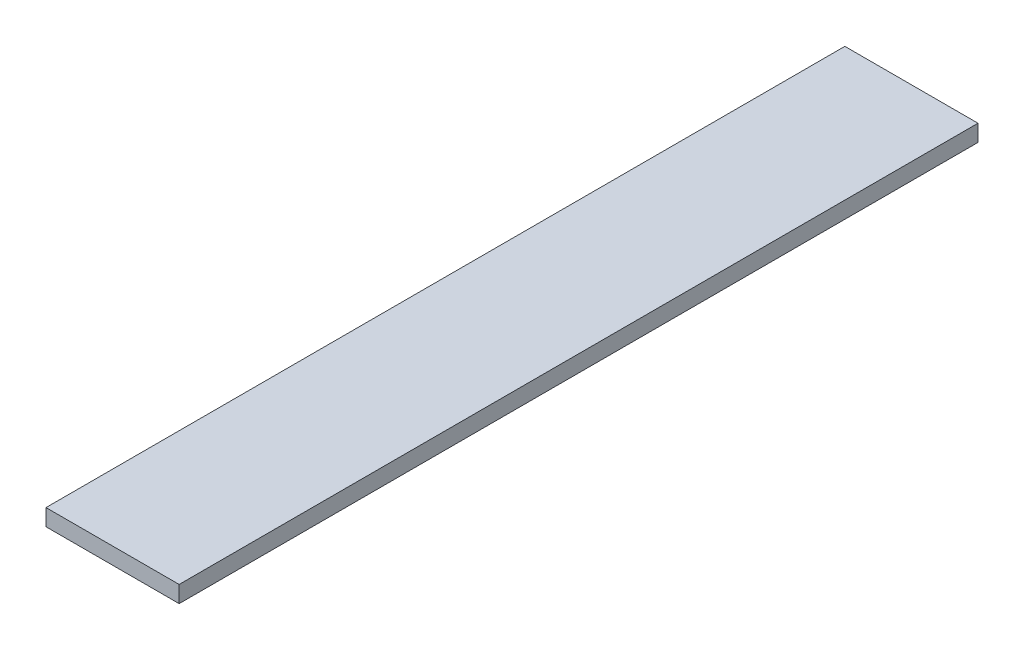
SolidWorks part; units mm, degrees
ref_plane "Front Plane" through (0, 0, 0) normal (0, 0, 1) x (1, 0, 0)
ref_plane "Top Plane" through (0, 0, 0) normal (0, 1, 0) x (1, 0, 0)
ref_plane "Right Plane" through (0, 0, 0) normal (1, 0, 0) x (0, 0, -1)
sketch "Sketch1" plane through (0, 0, 0) normal (0, 0, 1) x (1, 0, 0)
  line L0 (0, 1.5875) -> (0, -1.5875)
  line L1 (-12.7, 0) -> (12.7, 0) construction
  point P6 (0, 0)
  dimension "Width" = 25.4
  dimension "Thk" = 3.175
sketch "Sketch2" plane through (0, 0, 0) normal (1, 0, 0) x (0, 0, -1)
  line L0 (76.2, 0) -> (-76.2, 0)
  point P4 (0, 0)
  dimension "Length" = 152.4
sketch "Sketch3" plane through (0, 0, 0) normal (0, 0, 1) x (1, 0, 0)
  line L1 (12.7, 1.5875) -> (-12.7, 1.5875)
  line L2 (12.7, 1.5875) -> (12.7, -1.5875)
  line L3 (12.7, -1.5875) -> (-12.7, -1.5875)
  line L4 (-12.7, 1.5875) -> (-12.7, -1.5875)
  line L5 (12.7, 1.5875) -> (-12.7, -1.5875) construction
  line L6 (12.7, -1.5875) -> (-12.7, 1.5875) construction
  point P0 (0, 0)
extrude "Boss-Extrude1" add sketch "Sketch3" along normal up to vertex (76.2 mm away) and the other way up to vertex (76.2 mm away) up to point (0, 0, 76.2) other way up to point (0, 0, -76.2)
